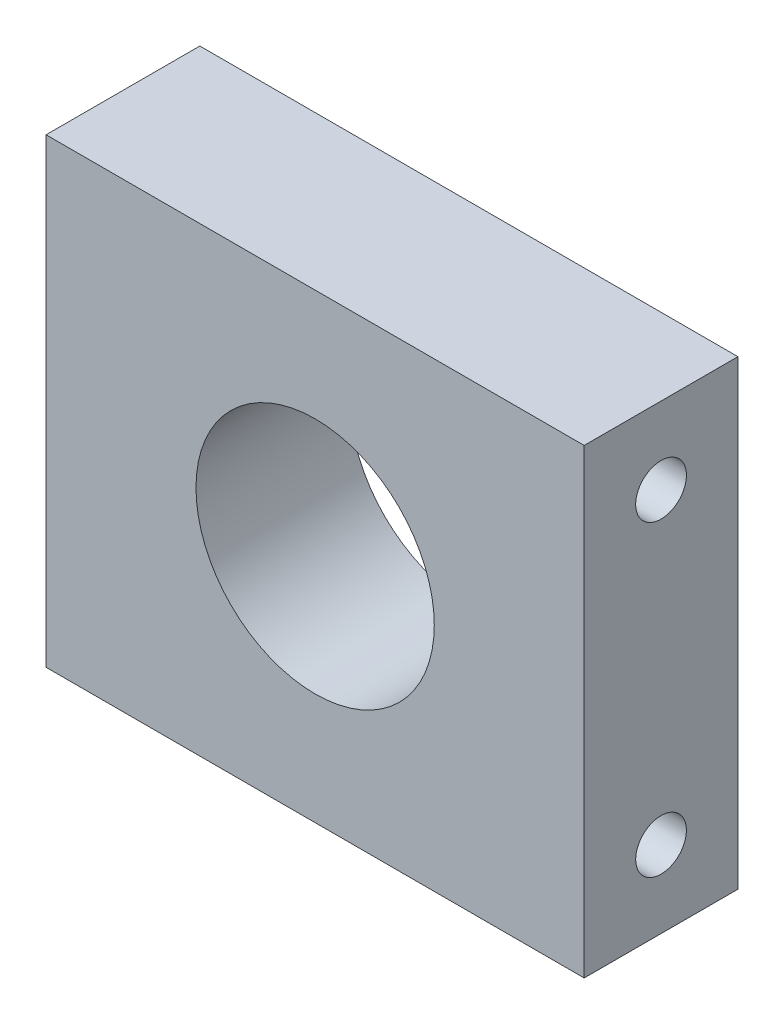
SolidWorks part; units mm, degrees
material "7079 Alloy"
ref_plane "Front Plane" through (0, 0, 0) normal (0, 0, 1) x (1, 0, 0)
ref_plane "Top Plane" through (0, 0, 0) normal (0, 1, 0) x (1, 0, 0)
ref_plane "Right Plane" through (0, 0, 0) normal (1, 0, 0) x (0, 0, -1)
sketch "Sketch1" plane through (0, 0, 0) normal (0, 0, 1) x (1, 0, 0)
  line L1 (17.5, -15) -> (-17.5, -15)
  line L2 (17.5, -15) -> (17.5, 15)
  line L3 (17.5, 15) -> (-17.5, 15)
  line L4 (-17.5, -15) -> (-17.5, 15)
  line L5 (17.5, -15) -> (-17.5, 15) construction
  line L6 (17.5, 15) -> (-17.5, -15) construction
  point P0 (0, 0)
  dimension "D1" = 35
  dimension "D2" = 30
extrude "Boss-Extrude1" add sketch "Sketch1" along normal blind 10
sketch "Sketch2" plane through (0, 0, 10) normal (0, 0, 1) x (1, 0, 0)
  circle A0 centre (0, 0) radius 7.75
  dimension "D1" = 15.5
extrude "Cut-Extrude1" cut sketch "Sketch2" against normal blind 10
sketch "Sketch3" plane through (17.5, 0, 0) normal (1, 0, 0) x (0, 0, -1)
  line L0 (-5, 15) -> (-5, -15) construction
  line L1 (-10, 15) -> (0, 15) construction
  line L2 (-10, -15) -> (0, -15) construction
  line L3 (0, 0) -> (-10, 0) construction
  line L4 (0, -15) -> (0, 15) construction
  line L5 (-10, -15) -> (-10, 15) construction
  circle A0 centre (-5, 10) radius 1.65
  circle A1 centre (-5, -10) radius 1.65
  dimension "D1" = 3.3
  dimension "D2" = 5
extrude "Cut-Extrude2" cut sketch "Sketch3" against normal blind 10
mirror "Mirror1" about plane through (0, 0, 0) normal (1, 0, 0) of "Cut-Extrude2"
